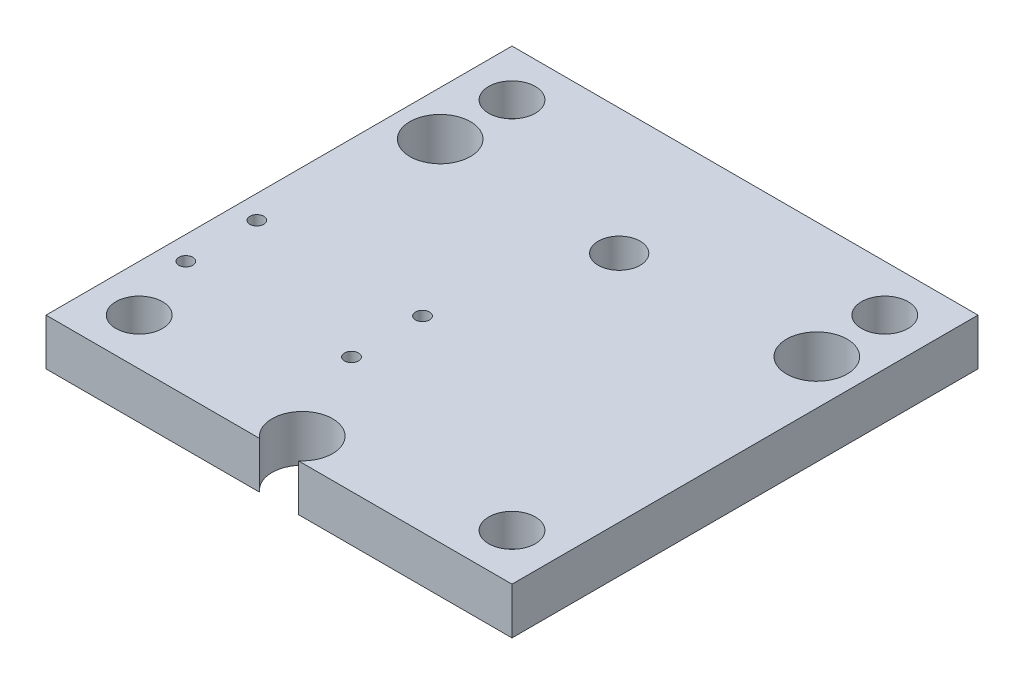
SolidWorks part; units mm, degrees
ref_plane "前视基准面" through (0, 0, 0) normal (0, 0, 1) x (1, 0, 0)
ref_plane "上视基准面" through (0, 0, 0) normal (0, 1, 0) x (1, 0, 0)
ref_plane "右视基准面" through (0, 0, 0) normal (1, 0, 0) x (0, 0, -1)
sketch "草图1" plane through (0, 0, 0) normal (0, 1, 0) x (1, 0, 0)
  line L1 (0, 0) -> (100, 0)
  line L2 (0, 0) -> (0, -100)
  line L3 (0, -100) -> (100, -100)
  line L4 (100, 0) -> (100, -100)
  dimension "D1" = 100
  dimension "D2" = 100
extrude "凸台-拉伸1" add sketch "草图1" along normal blind 10
sketch "草图2" plane through (0, 10, 0) normal (0, 1, 0) x (1, 0, 0)
  line L0 (10, -10) -> (90, -10) construction
  line L1 (90, -10) -> (90, -90) construction
  line L2 (90, -90) -> (10, -90) construction
  line L3 (10, -90) -> (10, -10) construction
  line L4 (50, -10) -> (50, 0) construction
  line L5 (100, 0) -> (0, 0) construction
  line L6 (10, -50) -> (0, -50) construction
  line L7 (0, 0) -> (0, -100) construction
  circle A0 centre (10, -10) radius 5
  circle A1 centre (90, -10) radius 5
  circle A2 centre (10, -90) radius 5
  circle A3 centre (90, -90) radius 5
  dimension "D2" = 10
  dimension "D1" = 80
extrude "切除-拉伸1" cut sketch "草图2" against normal blind 7
sketch "草图3" plane through (0, 10, 0) normal (0, 1, 0) x (1, 0, 0)
  line L0 (50, -95) -> (90.4145, -25) construction
  line L1 (90.4145, -25) -> (9.5855, -25) construction
  line L2 (9.5855, -25) -> (50, -95) construction
  line L3 (0, -100) -> (100, -100) construction
  line L4 (50, -25) -> (50, 0) construction
  line L6 (100, 0) -> (0, 0) construction
  circle A0 centre (50, -95) radius 6.5
  circle A1 centre (90.4145, -25) radius 6.5
  circle A2 centre (9.5855, -25) radius 6.5
  dimension "D3" = 13
  dimension "D1" = 70
  dimension "D2" = 5
extrude "切除-拉伸2" cut sketch "草图3" against normal through all
sketch "草图4" plane through (0, 10, 0) normal (0, 1, 0) x (1, 0, 0)
  line L0 (50, -27) -> (50, -95) construction
  circle A0 centre (50, -27) radius 4.5
  circle A1 centre (90.4145, -25) radius 6.5 construction
  dimension "D2" = 9
  dimension "D1" = 2
extrude "切除-拉伸3" cut sketch "草图4" against normal through all
sketch "草图5" plane through (0, 0, 0) normal (0, -1, 0) x (-1, 0, 0)
  circle A0 centre (-50, -27) radius 6.5
  dimension "D1" = 13
extrude "切除-拉伸4" cut sketch "草图5" against normal blind 3
sketch "草图6" plane through (0, 10, 0) normal (0, 1, 0) x (1, 0, 0)
  line L0 (40.56, -59.76) -> (40.56, -75) construction
  line L1 (40.56, -75) -> (5, -75) construction
  line L2 (5, -75) -> (5, -59.76) construction
  line L3 (5, -59.76) -> (40.56, -59.76) construction
  line L4 (0, 0) -> (0, -100) construction
  line L5 (0, -100) -> (45.8467, -100) construction
  circle A0 centre (40.56, -59.76) radius 1.5
  circle A1 centre (40.56, -75) radius 1.5
  circle A2 centre (5, -59.76) radius 1.5
  circle A3 centre (5, -75) radius 1.5
  dimension "D3" = 3
  dimension "D1" = 35.56
  dimension "D2" = 15.24
  dimension "D4" = 5
  dimension "D5" = 25
extrude "切除-拉伸5" cut sketch "草图6" against normal through all
sketch "草图7" plane through (0, 0, 0) normal (0, -1, 0) x (-1, 0, 0)
  line L0 (-50, -27) -> (49950, -27) construction
  circle A0 centre (-65, -27) radius 1.4
  circle A1 centre (-35, -27) radius 1.4
  circle A2 centre (-50, -27) radius 4.5 construction
  dimension "D1" = 2.8
  dimension "D2" = 15
  dimension "D3" = 15
extrude "切除-拉伸6" cut sketch "草图7" against normal blind 5
sketch "草图8" plane through (0, 0, 0) normal (0, -1, 0) x (1, 0, 0)
  line L0 (65, 27) -> (65, 50027) construction
  line L1 (50, 27) -> (50, 50027) construction
  dimension "D1" = 15
